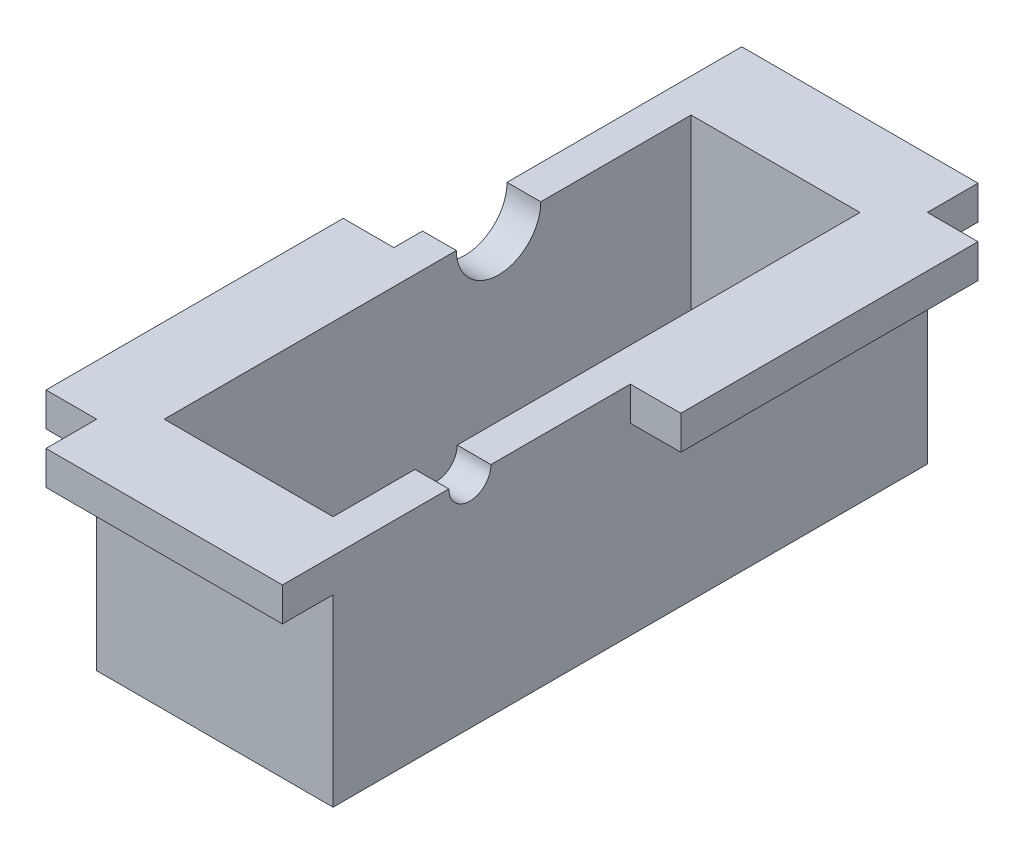
SolidWorks part; units mm, degrees
ref_plane "Front Plane" through (0, 0, 0) normal (0, 0, 1) x (1, 0, 0)
ref_plane "Top Plane" through (0, 0, 0) normal (0, 1, 0) x (1, 0, 0)
ref_plane "Right Plane" through (0, 0, 0) normal (1, 0, 0) x (0, 0, -1)
sketch "Sketch2" plane through (0, 0, 0) normal (0, 1, 0) x (1, 0, 0)
  line L1 (-6.35, 19.812) -> (6.35, 19.812)
  line L2 (-6.35, 19.812) -> (-6.35, -19.812)
  line L3 (-6.35, -19.812) -> (6.35, -19.812)
  line L4 (6.35, 19.812) -> (6.35, -19.812)
  line L5 (-6.35, 19.812) -> (6.35, -19.812) construction
  line L6 (-6.35, -19.812) -> (6.35, 19.812) construction
  line L7 (-8.89, 22.352) -> (8.89, 22.352)
  line L8 (-8.89, 22.352) -> (-8.89, -22.352)
  line L9 (-8.89, -22.352) -> (8.89, -22.352)
  line L10 (8.89, 22.352) -> (8.89, -22.352)
  line L11 (-8.89, 22.352) -> (8.89, -22.352) construction
  line L12 (-8.89, -22.352) -> (8.89, 22.352) construction
  point P0 (0, 0)
  point P6 (0, 0)
  dimension "D1" = 12.7
  dimension "D2" = 39.624
  dimension "D3" = 2.54
  dimension "D4" = 2.54
extrude "Boss-Extrude3" add sketch "Sketch2" along normal blind 16.383
sketch "Sketch4" plane through (0, 0, 0) normal (0, -1, 0) x (1, 0, 0)
  line L1 (-6.35, -19.812) -> (6.35, -19.812)
  line L2 (-6.35, -19.812) -> (-6.35, 19.812)
  line L3 (-6.35, 19.812) -> (6.35, 19.812)
  line L4 (6.35, -19.812) -> (6.35, 19.812)
  line L5 (-6.35, -19.812) -> (6.35, 19.812) construction
  line L6 (-6.35, 19.812) -> (6.35, -19.812) construction
  point P0 (0, 0)
extrude "Boss-Extrude4" add sketch "Sketch4" against normal blind 1.27
sketch "Sketch7" plane through (-8.89, 0, 0) normal (-1, 0, 0) x (0, 0, 1)
  line L0 (-22.352, 16.383) -> (22.352, 16.383) construction
  circle A0 centre (-5.334, 16.383) radius 3.175
  dimension "D1" = 6.35
  dimension "D2" = 14.478
extrude "Cut-Extrude1" cut sketch "Sketch7" against normal blind 4.318
sketch "Sketch8" plane through (8.89, 0, 0) normal (1, 0, 0) x (0, 0, -1)
  line L0 (-22.352, 16.383) -> (22.352, 16.383) construction
  circle A0 centre (-12.065, 16.383) radius 1.5875
  dimension "D1" = 3.175
  dimension "D2" = 7.747
extrude "Cut-Extrude2" cut sketch "Sketch8" against normal blind 4.318
sketch "Sketch9" plane through (0, 16.383, 0) normal (0, 1, 0) x (1, 0, 0)
  line L1 (-8.89, 22.352) -> (8.8774, 22.352)
  line L2 (-8.89, 22.352) -> (-8.89, 26.162)
  line L3 (-8.89, 26.162) -> (8.8774, 26.162)
  line L4 (8.8774, 22.352) -> (8.8774, 26.162)
  line L5 (8.89, -22.352) -> (-8.89, -22.352)
  line L6 (8.89, -22.352) -> (8.89, -26.162)
  line L7 (8.89, -26.162) -> (-8.89, -26.162)
  line L8 (-8.89, -22.352) -> (-8.89, -26.162)
  line L9 (8.8774, 22.352) -> (12.6874, 22.352)
  line L10 (8.8774, 22.352) -> (8.8774, 0)
  line L11 (8.8774, 0) -> (12.6874, 0)
  line L12 (12.6874, 22.352) -> (12.6874, 0)
  line L13 (-8.89, -22.352) -> (-12.7, -22.352)
  line L14 (-8.89, -22.352) -> (-8.89, 0)
  line L15 (-8.89, 0) -> (-12.7, 0)
  line L16 (-12.7, -22.352) -> (-12.7, 0)
  point P16 (-8.89, -23.8438)
  point P18 (8.8774, 22.352)
  dimension "D1" = 3.81
  dimension "D2" = 3.81
  dimension "D3" = 3.81
  dimension "D4" = 3.81
extrude "Boss-Extrude5" add sketch "Sketch9" against normal blind 2.54 contours L2 L1 L4 L3 | L10 L9 L12 L11 | L6 L5 L8 L7 | L14 L13 L16 L15
equation "\"Tin\"= 0.469"
equation "\"Tout\"= 1.25"
equation "\"Nout\"= 1100"
equation "\"Din\"= .125in"
equation "\"Dout\"= .25in"
equation "\"Shaft Length\"= 1in"
equation "\"Shear Stress in\"= 1222.96"
equation "\"Shear Stress out\"= 407.44"
equation "\"Ft in&out\"= 2.5"
equation "\"Fr\"= .910"
equation "\"Vout\"= 72"
equation "\"Vin\"= 96"
equation "\"Nin\"= 2933.33"
equation "\"Pressure in\"= 19.41"
equation "\"Pressure out\"= 9.71"
equation "\"PV\"= 1863.68"
equation "\"t in & out\"= 0.001213"
equation "\"ODin\"= 0.127in"
equation "\"ODout\"= .252"
equation "\"1of4 OD\"= 1.04in"
equation "\"1of8 OD \"= 0.42"
equation "\"height housing 1of4\"= \"1of4 OD\" + 0.15"
equation "\"height housing\"= 0.57"
equation "\"center distance\"= .6875"
equation "\"width\"= .50"
equation "\"D1@Sketch2\"=\"width\""
equation "\"length\"= 1.56in"
equation "\"D2@Sketch2\"=\"length\""
equation "\"housing thickness\"= .1"
equation "\"D3@Sketch2\"=\"housing thickness\""
equation "\"D1@Boss-Extrude3\"=\"height housing 1of4\"/2+0.05"
equation "\"D1@Sketch7\"=\"Dout\""
equation "\"D1@Sketch8\"=\"Din\""
